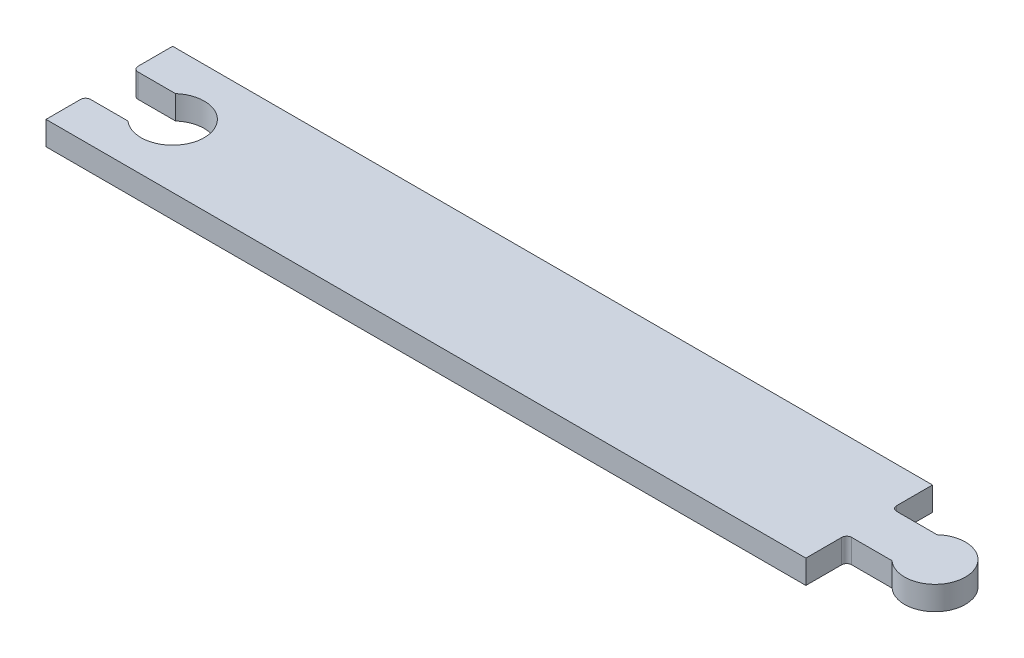
SolidWorks part; units mm, degrees
ref_plane "Front Plane" through (0, 0, 0) normal (0, 0, 1) x (1, 0, 0)
ref_plane "Top Plane" through (0, 0, 0) normal (0, 1, 0) x (1, 0, 0)
ref_plane "Right Plane" through (0, 0, 0) normal (1, 0, 0) x (0, 0, -1)
sketch "Sketch1" plane through (0, 0, 0) normal (0, 1, 0) x (1, 0, 0)
  line L0 (-76.2, 0) -> (95.5, 0) construction
  line L1 (-76.2, -12.7) -> (76.2, -12.7)
  line L2 (-76.2, -12.7) -> (-76.2, -4.7625)
  line L3 (-76.2, 12.7) -> (76.2, 12.7)
  line L4 (76.2, -12.7) -> (76.2, -4.5125)
  line L5 (-76.2, -12.7) -> (76.2, 12.7) construction
  line L6 (-76.2, 12.7) -> (76.2, -12.7) construction
  line L7 (76.2, 4.5125) -> (85.2954, 4.5125)
  line L8 (76.2, -4.5125) -> (85.2954, -4.5125)
  line L9 (76.2, 4.5125) -> (76.2, 12.7)
  line L10 (-67.7001, 4.7625) -> (-76.2, 4.7625)
  line L11 (-76.2, -4.7625) -> (-67.7001, -4.7625)
  line L12 (-76.2, 4.7625) -> (-76.2, 12.7)
  arc A0 (-67.7001, -4.7625) -> (-67.7001, 4.7625) centre (-63.5, 0) ccw
  arc A1 (85.2954, -4.5125) -> (85.2954, 4.5125) centre (89.4, 0) ccw
  point P0 (0, 0)
  dimension "D5" = 12.7
  dimension "D6" = 12.2
  dimension "D1" = 152.4
  dimension "D2" = 25.4
  dimension "D3" = 12.7
  dimension "D4" = 13.2
  dimension "D7" = 9.025
  dimension "D8" = 4.5125
  dimension "D9" = 9.525
  dimension "D10" = 4.7625
extrude "Boss-Extrude1" add sketch "Sketch1" along normal blind 4.7625
fillet "Fillet1" radius 1 4 edges at (-76.2, 2.3813, 4.7625) (-76.2, 2.3813, -4.7625) (76.2, 2.3813, -4.5125) (76.2, 2.3813, 4.5125)
